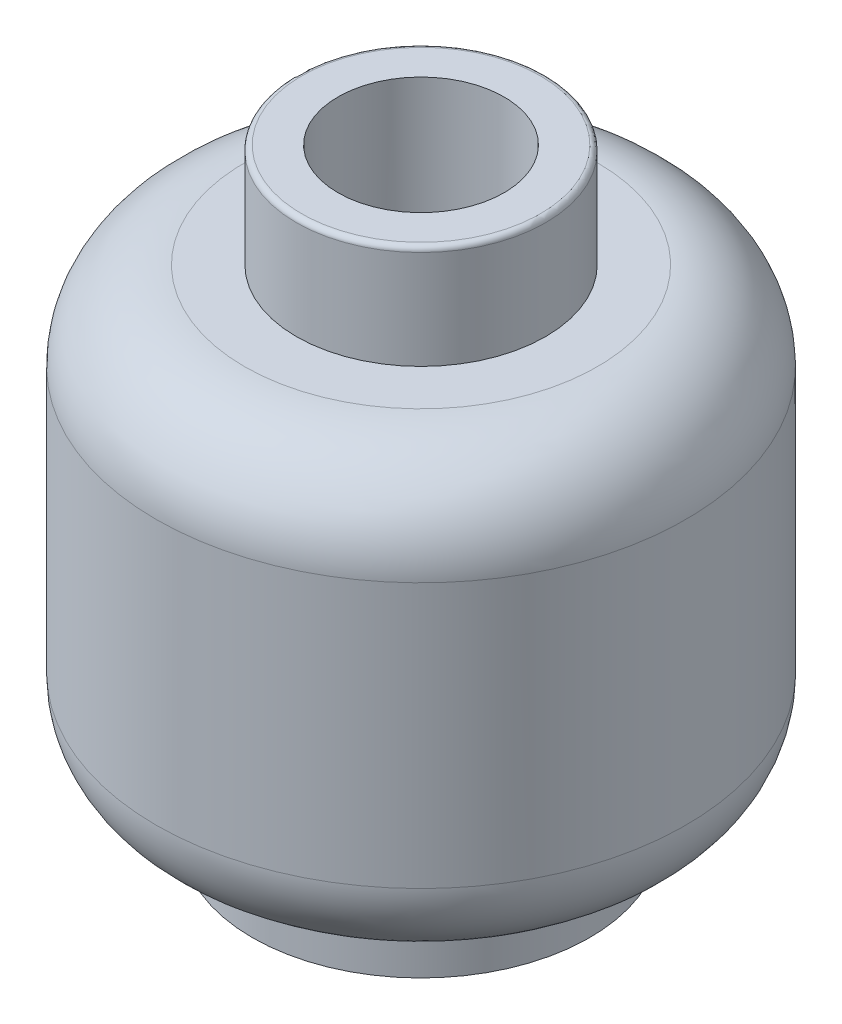
SolidWorks part; units mm, degrees
ref_plane "Front Plane" through (0, 0, 0) normal (0, 0, 1) x (1, 0, 0)
ref_plane "Top Plane" through (0, 0, 0) normal (0, 1, 0) x (1, 0, 0)
ref_plane "Right Plane" through (0, 0, 0) normal (1, 0, 0) x (0, 0, -1)
sketch "Sketch1" plane through (0, 0, 0) normal (0, 0, 1) x (1, 0, 0)
  line L0 (0, 161.3158) -> (0, -142.3684) construction
  line L1 (0, 11.6) -> (2.4, 11.6)
  line L2 (2.4, 11.6) -> (2.4, 9.6)
  line L3 (2.4, 9.6) -> (5.1, 9.6)
  line L4 (5.1, 9.6) -> (5.1, 1.1)
  line L5 (5.1, 1.1) -> (3.25, 1.1)
  line L6 (3.25, 1.1) -> (3.25, 0)
  line L7 (3.25, 0) -> (0, 0)
  line L8 (0, 11.6) -> (0, 0)
  dimension "D1" = 2
  dimension "D2" = 1.1
  dimension "D3" = 9.6
  dimension "D4" = 5.1
  dimension "D5" = 3.25
  dimension "D6" = 2.4
revolve "Revolve1" add sketch "Sketch1" angle 360 about L0
fillet "Fillet1" radius 1.7 2 edges at (0, 1.1, 5.1) (0, 9.6, 5.1)
sketch "Sketch2" plane through (0, 11.6, 0) normal (0, 1, 0) x (1, 0, 0)
  circle A0 centre (0, 0) radius 1.6
  dimension "D1" = 3.2
extrude "Cut-Extrude1" cut sketch "Sketch2" against normal blind 2
sketch "Sketch3" plane through (0, 9.6, 0) normal (0, 1, 0) x (1, 0, 0)
  line L0 (0, -6.1928) -> (0, 6.2106) construction
  line L1 (-6.4797, 0) -> (6.5439, 0) construction
  line L2 (-0.42, 1.5439) -> (-0.42, 0.2425)
  line L3 (-0.42, 0.2425) -> (-1.547, -0.4082)
  line L4 (0, 0) -> (-7.4467, -4.2994) construction
  line L5 (0, 0) -> (6.4472, 3.7223) construction
  line L6 (0, 0) -> (3.8818, -6.7235) construction
  line L7 (0, 0) -> (-4.1167, 7.1303) construction
  line L8 (1.547, -0.4082) -> (0.42, 0.2425)
  line L9 (0.42, 0.2425) -> (0.42, 1.5439)
  line L10 (-1.127, -1.1357) -> (0, -0.485)
  line L11 (0, -0.485) -> (1.127, -1.1357)
  line L12 (0, 0) -> (-0.42, 0.2425) construction
  circle A0 centre (0, 0) radius 1.6 construction
  circle A2 centre (0, 0) radius 1.6
  point P12 (0, 0)
  circle M14 centre (0, 0) radius 1.6
  dimension "D1" = 120
  dimension "D2" = 0.42
  dimension "D4" = 0.485
  dimension "D3" = 3
extrude "Cut-Extrude2" cut sketch "Sketch3" against normal through all contours L3 L2 M14 | L9 L8 M14 | L11 L10 M14
sketch "Sketch4" plane through (0, 0, 0) normal (0, -1, 0) x (1, 0, 0)
  circle A0 centre (0, 0) radius 2.45
  dimension "D1" = 4.9
extrude "Cut-Extrude3" cut sketch "Sketch4" against normal offset from surface (8.5 mm away) 3.1 up to face at (0, 11.6, 1.6)
sketch "Sketch5" plane through (0, 0, 0) normal (0, 0, 1) x (1, 0, 0)
  line L0 (-5.1, 6.5) -> (-2.25, 6.5) construction
  line L1 (-6.607, 4.5) -> (6.607, 4.5) construction
  line L2 (-5.1, 7.9) -> (-5.1, 2.8) construction
  line L3 (5.1, 6.5) -> (2.25, 6.5) construction
  line L4 (5.1, 2.8) -> (5.1, 7.9) construction
  line L5 (0, -4.1986) -> (0, 17.0944) construction
  line L6 (5.1, 2.8) -> (-5.1, 2.8) construction
  circle A0 centre (-2.25, 6.5) radius 0.7473
  circle A1 centre (2.25, 6.5) radius 0.7473
  arc A2 (2.25, 4.5) -> (-2.25, 4.5) centre (0, 6.3166) cw construction
  arc A3 (-2.539, 4.2667) -> (2.539, 4.2667) centre (0, 6.3166) ccw
  arc A4 (-1.961, 4.7333) -> (1.961, 4.7333) centre (0, 6.3166) ccw
  arc A5 (-1.961, 4.7333) -> (-2.539, 4.2667) centre (-2.25, 4.5) ccw
  arc A6 (2.539, 4.2667) -> (1.961, 4.7333) centre (2.25, 4.5) ccw
  point P11 (0, 4.5)
  point P19 (0, 3.4248)
  point P24 (0, 0)
  point P25 (2.25, 4.5)
  point P26 (0, 0)
  point P27 (0, 0)
  point P28 (0, 0)
  point P29 (0, 0)
  point P30 (-2.25, 4.5)
  point P31 (2.25, 4.5)
  point P32 (0, 0)
  point P33 (0, 0)
  point P34 (0, 3.4404)
  point P35 (0, 3.0534)
  point P38 (0, 3.4248)
  dimension "D3" = 1.4945
  dimension "D4" = 0.2534
  dimension "D5" = 0.3714
  dimension "D1" = 4.5
  dimension "D2" = 4.5
  dimension "2" = 2
ref_plane "Plane1" through (0, 0, 5.1) normal (0, 0, 1) x (1, 0, 0)
split line "Split Line2"
fillet "Fillet2" radius 0.1 1 edges at (0, 11.6, 2.4)
